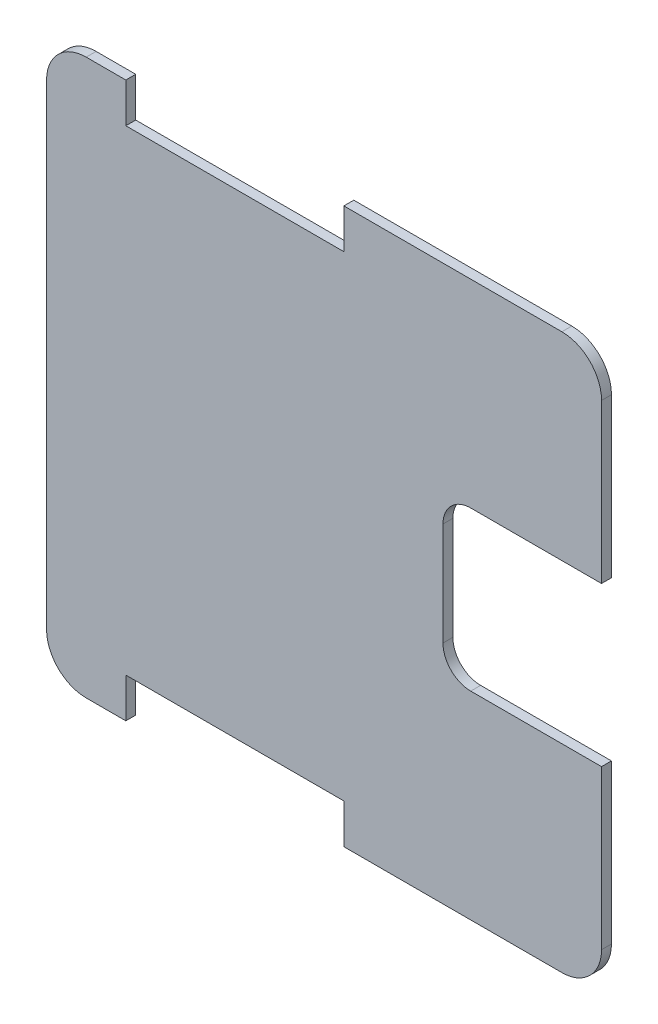
SolidWorks part; units mm, degrees
ref_plane "Front Plane" through (0, 0, 0) normal (0, 0, 1) x (1, 0, 0)
ref_plane "Top Plane" through (0, 0, 0) normal (0, 1, 0) x (1, 0, 0)
ref_plane "Right Plane" through (0, 0, 0) normal (1, 0, 0) x (0, 0, -1)
sketch "Sketch1" plane through (0, 0, 0) normal (0, 0, 1) x (1, 0, 0)
  line L1 (25.4, 0) -> (330.2, 0)
  line L2 (0, 25.4) -> (0, 330.2)
  line L3 (25.4, 355.6) -> (330.2, 355.6)
  line L4 (355.6, 25.4) -> (355.6, 330.2)
  arc A0 (25.4, 0) -> (0, 25.4) centre (25.4, 25.4) cw
  arc A1 (330.2, 0) -> (355.6, 25.4) centre (330.2, 25.4) ccw
  arc A2 (330.2, 355.6) -> (355.6, 330.2) centre (330.2, 330.2) cw
  arc A3 (0, 330.2) -> (25.4, 355.6) centre (25.4, 330.2) cw
  point P7 (0, 0)
  point P10 (355.6, 0)
  point P15 (0, 355.6)
  dimension "D3" = 25.4
  dimension "D1" = 355.6
  dimension "D2" = 355.6
extrude "Boss-Extrude1" add sketch "Sketch1" along normal blind 6.35
sketch "Sketch2" plane through (0, 0, 0) normal (0, 0, -1) x (-1, 0, 0)
  line L0 (-330.2, 355.6) -> (-25.4, 355.6) construction
  line L1 (-190.5, 355.6) -> (-50.8, 355.6)
  line L2 (-190.5, 355.6) -> (-190.5, 330.2)
  line L3 (-190.5, 330.2) -> (-50.8, 330.2)
  line L4 (-50.8, 355.6) -> (-50.8, 330.2)
  line L5 (-190.5, 25.4) -> (-50.8, 25.4)
  line L6 (-190.5, 25.4) -> (-190.5, 0)
  line L7 (-190.5, 0) -> (-50.8, 0)
  line L8 (-50.8, 25.4) -> (-50.8, 0)
  line L9 (-25.4, 0) -> (-330.2, 0) construction
  line L11 (0, 330.2) -> (0, 25.4) construction
  dimension "D1" = 25.4
  dimension "D2" = 25.4
  dimension "D3" = 139.7
  dimension "D4" = 50.8
extrude "Cut-Extrude1" cut sketch "Sketch2" against normal through all
sketch "Sketch3" plane through (0, 0, 0) normal (0, 0, -1) x (-1, 0, 0)
  line L1 (-355.6, 25.4) -> (-355.6, 330.2) construction
  line L2 (-355.6, 127) -> (-271.78, 127)
  line L3 (-355.6, 127) -> (-355.6, 228.6)
  line L4 (-355.6, 228.6) -> (-271.78, 228.6)
  line L6 (-254, 144.78) -> (-254, 210.82)
  line L7 (-330.2, 355.6) -> (-190.5, 355.6) construction
  arc A0 (-271.78, 127) -> (-254, 144.78) centre (-271.78, 144.78) ccw
  arc A1 (-271.78, 228.6) -> (-254, 210.82) centre (-271.78, 210.82) cw
  point P10 (-254, 127)
  point P13 (-254, 228.6)
  dimension "D4" = 17.78
  dimension "D1" = 101.6
  dimension "D2" = 101.6
  dimension "D3" = 127
extrude "Cut-Extrude2" cut sketch "Sketch3" against normal through all
